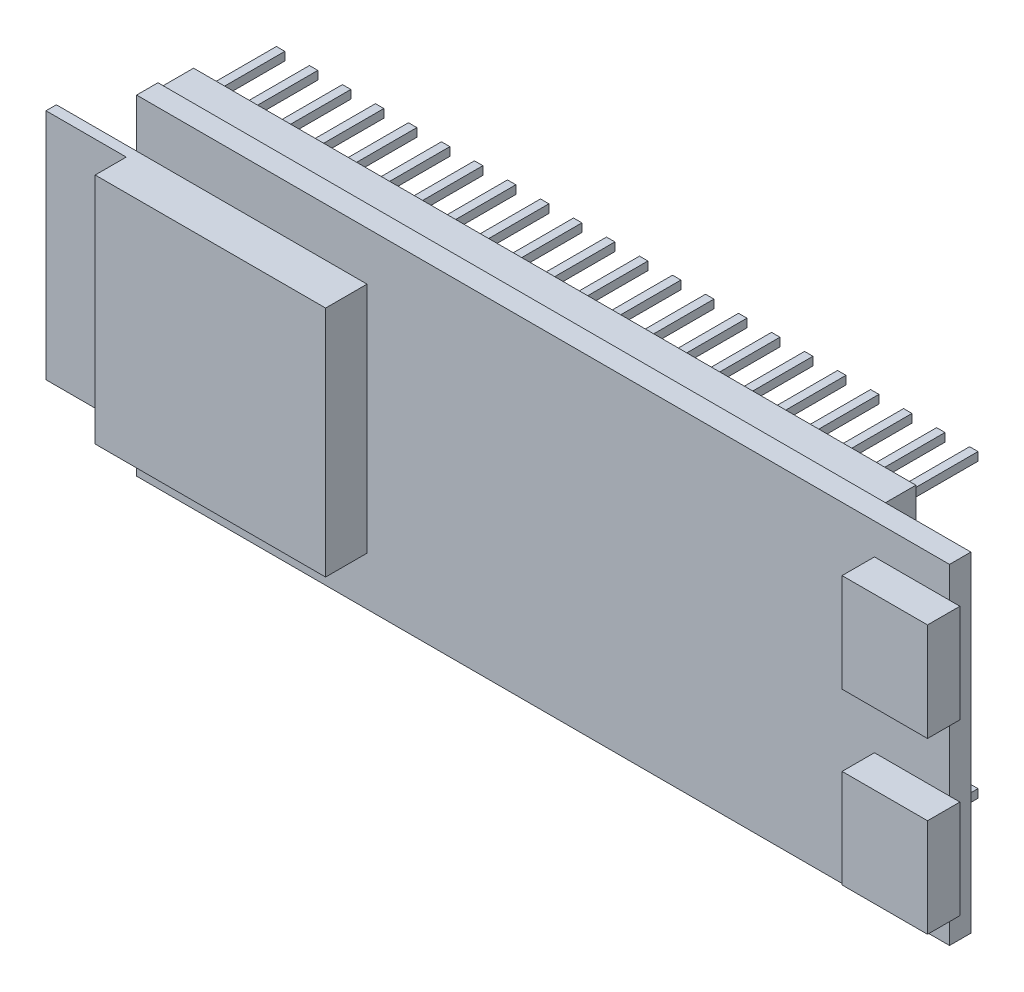
SolidWorks part; units mm, degrees
ref_plane "Front Plane" through (0, 0, 0) normal (0, 0, 1) x (1, 0, 0)
ref_plane "Top Plane" through (0, 0, 0) normal (0, 1, 0) x (1, 0, 0)
ref_plane "Right Plane" through (0, 0, 0) normal (1, 0, 0) x (0, 0, -1)
sketch "Sketch1" plane through (0, 0, 0) normal (0, 0, 1) x (1, 0, 0)
  line L1 (-31.4, 12.75) -> (31.4, 12.75)
  line L2 (-31.4, 12.75) -> (-31.4, -12.75)
  line L3 (-31.4, -12.75) -> (31.4, -12.75)
  line L4 (31.4, 12.75) -> (31.4, -12.75)
  line L5 (-31.4, 12.75) -> (31.4, -12.75) construction
  line L6 (-31.4, -12.75) -> (31.4, 12.75) construction
  point P0 (0, 0)
  dimension "D1" = 62.8
  dimension "D2" = 25.5
extrude "Boss-Extrude1" add sketch "Sketch1" along normal mid plane 1.65
sketch "Sketch2" plane through (0, 0, 0.825) normal (0, 0, 1) x (1, 0, 0)
  line L0 (0, 0) -> (-31.4, 0) construction
  line L2 (-37.6, 9) -> (-25.2, 9)
  line L3 (-37.6, 9) -> (-37.6, -9)
  line L4 (31.4, -12.75) -> (31.4, 12.75)
  line L5 (31.4, 12.75) -> (-31.4, 12.75)
  line L6 (-31.4, 12.75) -> (-31.4, -12.75)
  line L7 (-31.4, -12.75) -> (31.4, -12.75)
  line L8 (31.4, -12.75) -> (31.4, 12.75)
  line L9 (31.4, 12.75) -> (-31.4, 12.75)
  line L10 (-31.4, 12.75) -> (-31.4, -12.75)
  line L11 (-31.4, -12.75) -> (31.4, -12.75)
  line L12 (-37.6, -9) -> (-25.2, -9)
  line L13 (-25.2, 9) -> (-25.2, -9)
  line L14 (-37.6, 9) -> (-25.2, -9) construction
  line L15 (-37.6, -9) -> (-25.2, 9) construction
  line L16 (-31.4, 9) -> (-13.6, 9)
  line L17 (-31.4, 9) -> (-31.4, -9)
  line L18 (-31.4, -9) -> (-13.6, -9)
  line L19 (-13.6, 9) -> (-13.6, -9)
  line L20 (-31.4, 9) -> (-13.6, -9) construction
  line L21 (-31.4, -9) -> (-13.6, 9) construction
  point P11 (-22.5, 0)
  line M15 (-31.4, 12.75) -> (-31.4, -12.75)
  dimension "D2" = 6.2
  dimension "D3" = 18
  dimension "D4" = 17.8
  dimension "D5" = 18
  dimension "D1" = 0
extrude "Boss-Extrude2" add sketch "Sketch2" along normal blind 0.8 contours L3 L12 L2 M15 | L13 L2 L12 M15 | L19 L16 L13 L18
sketch "Sketch3" plane through (0, 0, 1.625) normal (0, 0, 1) x (1, 0, 0)
  line L4 (-13.6, 9) -> (-31.4, 9)
  line L5 (-13.6, -9) -> (-13.6, 9)
  line L6 (-31.4, -9) -> (-13.6, -9)
  line L7 (-31.4, 9) -> (-31.4, -9)
  line L8 (-13.6, 9) -> (-31.4, 9)
  line L9 (-13.6, -9) -> (-13.6, 9)
  line L10 (-31.4, -9) -> (-13.6, -9)
  line L11 (-31.4, 9) -> (-31.4, -9)
  line L12 (31.4, -12.75) -> (31.4, 12.75)
  line L13 (31.4, 12.75) -> (-31.4, 12.75)
  line L14 (-31.4, 12.75) -> (-31.4, -12.75)
  line L15 (-31.4, -12.75) -> (31.4, -12.75)
  line L16 (31.4, -12.75) -> (31.4, 12.75)
  line L17 (31.4, 12.75) -> (-31.4, 12.75)
  line L18 (-31.4, 12.75) -> (-31.4, -12.75)
  line L19 (-31.4, -12.75) -> (31.4, -12.75)
  line L20 (-25.2, 9) -> (-37.6, 9)
  line L21 (-25.2, -9) -> (-25.2, 9)
  line L22 (-37.6, -9) -> (-25.2, -9)
  line L23 (-37.6, 9) -> (-37.6, -9)
  line L24 (-25.2, 9) -> (-37.6, 9)
  line L25 (-25.2, -9) -> (-25.2, 9)
  line L26 (-37.6, -9) -> (-25.2, -9)
  line L27 (-37.6, 9) -> (-37.6, -9)
  line M14 (-37.6, -9) -> (-13.6, -9)
  line M15 (-13.6, -9) -> (-13.6, 9)
  line M16 (-13.6, 9) -> (-37.6, 9)
  dimension "D1" = 0
  dimension "D2" = 0
  dimension "D3" = 0
extrude "Boss-Extrude3" add sketch "Sketch3" along normal offset from surface (2.4 mm away) 3.2 contours L25 L8 L11 M14 | L25 L10 M15 M16 up to face at (-11.25, 0, 0.825) offset beyond the face yes
sketch "Sketch5" plane through (0, 0, 0.825) normal (0, 0, 1) x (1, 0, 0)
  line L0 (0, 0) -> (31.4, 0) construction
  line L1 (31.4, -12.75) -> (31.4, 12.75) construction
  line L2 (28.9, 12.75) -> (28.9, 0) construction
  line L3 (31.4, 12.75) -> (-31.4, 12.75) construction
  line L4 (25.6, -2.75) -> (32.2, -2.75)
  line L5 (25.6, 10.35) -> (32.2, 10.35)
  line L6 (25.6, 10.35) -> (25.6, 2.75)
  line L7 (25.6, 2.75) -> (32.2, 2.75)
  line L8 (32.2, 10.35) -> (32.2, 2.75)
  line L9 (25.6, 10.35) -> (32.2, 2.75) construction
  line L10 (25.6, 2.75) -> (32.2, 10.35) construction
  line L11 (32.2, -10.35) -> (32.2, -2.75)
  line L12 (25.6, -10.35) -> (32.2, -10.35)
  line L13 (25.6, -10.35) -> (25.6, -2.75)
  point P9 (28.9, 6.55)
  dimension "D1" = 7.6
  dimension "D2" = 6.6
  dimension "D3" = 0.8
  dimension "D4" = 2.4
extrude "Boss-Extrude4" add sketch "Sketch5" along normal blind 2.5
sketch "Sketch6" plane through (0, 0, -0.825) normal (0, 0, -1) x (-1, 0, 0)
  line L0 (-31.2, 12.55) -> (-31.2, -12.55)
  line L1 (-31.2, -12.55) -> (31.2, -12.55)
  line L2 (31.2, -12.55) -> (31.2, 12.55)
  line L3 (31.2, 12.55) -> (-31.2, 12.55)
  line L4 (-31.4, 12.75) -> (-31.4, -12.75)
  line L5 (-31.4, -12.75) -> (31.4, -12.75)
  line L6 (31.4, -12.75) -> (31.4, 12.75)
  line L7 (31.4, 12.75) -> (-31.4, 12.75)
  line L8 (-31.4, 12.75) -> (-31.4, -12.75) construction
  line L9 (-31.4, -12.75) -> (31.4, -12.75) construction
  line L10 (31.4, -12.75) -> (31.4, 12.75) construction
  line L11 (31.4, 12.75) -> (-31.4, 12.75) construction
  line L12 (-31.2, 10) -> (31.2, 10)
  line L13 (-31.2, 0) -> (31.2, 0) construction
  line L14 (-31.2, -10) -> (31.2, -10)
  dimension "D3" = 2.55
  dimension "D1" = 0
  dimension "D2" = 0.2
extrude "Boss-Extrude5" add sketch "Sketch6" along normal blind 2.55 contours L0 L12 L2 L3 | L14 L0 L1 L2
sketch "Sketch7" plane through (0, 0, -3.375) normal (0, 0, -1) x (-1, 0, 0)
  line L0 (31.2, -10) -> (-31.2, -10) construction
  line L1 (-31.2, -10) -> (-31.2, -12.55) construction
  line L2 (-31.2, -12.55) -> (31.2, -12.55) construction
  line L3 (31.2, -12.55) -> (31.2, -10) construction
  line L4 (-31.2, 12.55) -> (-31.2, 10) construction
  line L5 (-31.2, 10) -> (31.2, 10) construction
  line L6 (31.2, 10) -> (31.2, 12.55) construction
  line L7 (31.2, 12.55) -> (-31.2, 12.55) construction
  line L8 (31.2, -10) -> (-31.2, -10) construction
  line L9 (-31.2, -10) -> (-31.2, -12.55) construction
  line L10 (-31.2, -12.55) -> (31.2, -12.55) construction
  line L11 (31.2, -12.55) -> (31.2, -10) construction
  line L12 (-31.2, 12.55) -> (-31.2, 10) construction
  line L13 (-31.2, 10) -> (31.2, 10) construction
  line L14 (31.2, 10) -> (31.2, 12.55) construction
  line L15 (31.2, 12.55) -> (-31.2, 12.55) construction
  line L16 (-31.2, 11.275) -> (31.2, 11.275) construction
  line L17 (-21.25, 11.6) -> (-21.25, 10.95)
  line L18 (-23.8, 11.6) -> (-23.15, 11.6)
  line L19 (-23.8, 11.6) -> (-23.8, 10.95)
  line L20 (-23.8, 10.95) -> (-23.15, 10.95)
  line L21 (-23.15, 11.6) -> (-23.15, 10.95)
  line L22 (-23.8, 11.6) -> (-23.15, 10.95) construction
  line L23 (-23.8, 10.95) -> (-23.15, 11.6) construction
  line L24 (-21.25, 11.6) -> (-20.6, 11.6)
  line L25 (-20.6, 11.6) -> (-20.6, 10.95)
  line L26 (-21.25, 10.95) -> (-20.6, 10.95)
  line L27 (-18.7, 11.6) -> (-18.7, 10.95)
  line L28 (-18.7, 11.6) -> (-18.05, 11.6)
  line L29 (-18.05, 11.6) -> (-18.05, 10.95)
  line L30 (-18.7, 10.95) -> (-18.05, 10.95)
  line L31 (-16.15, 11.6) -> (-16.15, 10.95)
  line L32 (-16.15, 11.6) -> (-15.5, 11.6)
  line L33 (-15.5, 11.6) -> (-15.5, 10.95)
  line L34 (-16.15, 10.95) -> (-15.5, 10.95)
  line L35 (-13.6, 11.6) -> (-13.6, 10.95)
  line L36 (-13.6, 11.6) -> (-12.95, 11.6)
  line L37 (-12.95, 11.6) -> (-12.95, 10.95)
  line L38 (-13.6, 10.95) -> (-12.95, 10.95)
  line L39 (-11.05, 11.6) -> (-11.05, 10.95)
  line L40 (-11.05, 11.6) -> (-10.4, 11.6)
  line L41 (-10.4, 11.6) -> (-10.4, 10.95)
  line L42 (-11.05, 10.95) -> (-10.4, 10.95)
  line L43 (-8.5, 11.6) -> (-8.5, 10.95)
  line L44 (-8.5, 11.6) -> (-7.85, 11.6)
  line L45 (-7.85, 11.6) -> (-7.85, 10.95)
  line L46 (-8.5, 10.95) -> (-7.85, 10.95)
  line L47 (-5.95, 11.6) -> (-5.95, 10.95)
  line L48 (-5.95, 11.6) -> (-5.3, 11.6)
  line L49 (-5.3, 11.6) -> (-5.3, 10.95)
  line L50 (-5.95, 10.95) -> (-5.3, 10.95)
  line L51 (-3.4, 11.6) -> (-3.4, 10.95)
  line L52 (-3.4, 11.6) -> (-2.75, 11.6)
  line L53 (-2.75, 11.6) -> (-2.75, 10.95)
  line L54 (-3.4, 10.95) -> (-2.75, 10.95)
  line L55 (-0.85, 11.6) -> (-0.85, 10.95)
  line L56 (-0.85, 11.6) -> (-0.2, 11.6)
  line L57 (-0.2, 11.6) -> (-0.2, 10.95)
  line L58 (-0.85, 10.95) -> (-0.2, 10.95)
  line L59 (1.7, 11.6) -> (1.7, 10.95)
  line L60 (1.7, 11.6) -> (2.35, 11.6)
  line L61 (2.35, 11.6) -> (2.35, 10.95)
  line L62 (1.7, 10.95) -> (2.35, 10.95)
  line L63 (4.25, 11.6) -> (4.25, 10.95)
  line L64 (4.25, 11.6) -> (4.9, 11.6)
  line L65 (4.9, 11.6) -> (4.9, 10.95)
  line L66 (4.25, 10.95) -> (4.9, 10.95)
  line L67 (6.8, 11.6) -> (6.8, 10.95)
  line L68 (6.8, 11.6) -> (7.45, 11.6)
  line L69 (7.45, 11.6) -> (7.45, 10.95)
  line L70 (6.8, 10.95) -> (7.45, 10.95)
  line L71 (9.35, 11.6) -> (9.35, 10.95)
  line L72 (9.35, 11.6) -> (10, 11.6)
  line L73 (10, 11.6) -> (10, 10.95)
  line L74 (9.35, 10.95) -> (10, 10.95)
  line L75 (11.9, 11.6) -> (11.9, 10.95)
  line L76 (11.9, 11.6) -> (12.55, 11.6)
  line L77 (12.55, 11.6) -> (12.55, 10.95)
  line L78 (11.9, 10.95) -> (12.55, 10.95)
  line L79 (14.45, 11.6) -> (14.45, 10.95)
  line L80 (14.45, 11.6) -> (15.1, 11.6)
  line L81 (15.1, 11.6) -> (15.1, 10.95)
  line L82 (14.45, 10.95) -> (15.1, 10.95)
  line L83 (17, 11.6) -> (17, 10.95)
  line L84 (17, 11.6) -> (17.65, 11.6)
  line L85 (17.65, 11.6) -> (17.65, 10.95)
  line L86 (17, 10.95) -> (17.65, 10.95)
  line L87 (19.55, 11.6) -> (19.55, 10.95)
  line L88 (19.55, 11.6) -> (20.2, 11.6)
  line L89 (20.2, 11.6) -> (20.2, 10.95)
  line L90 (19.55, 10.95) -> (20.2, 10.95)
  line L91 (22.1, 11.6) -> (22.1, 10.95)
  line L92 (22.1, 11.6) -> (22.75, 11.6)
  line L93 (22.75, 11.6) -> (22.75, 10.95)
  line L94 (22.1, 10.95) -> (22.75, 10.95)
  line L95 (24.65, 11.6) -> (24.65, 10.95)
  line L96 (24.65, 11.6) -> (25.3, 11.6)
  line L97 (25.3, 11.6) -> (25.3, 10.95)
  line L98 (24.65, 10.95) -> (25.3, 10.95)
  line L99 (27.2, 11.6) -> (27.2, 10.95)
  line L100 (27.2, 11.6) -> (27.85, 11.6)
  line L101 (27.85, 11.6) -> (27.85, 10.95)
  line L102 (27.2, 10.95) -> (27.85, 10.95)
  line L103 (29.75, 11.6) -> (29.75, 10.95)
  line L104 (29.75, 11.6) -> (30.4, 11.6)
  line L105 (30.4, 11.6) -> (30.4, 10.95)
  line L106 (29.75, 10.95) -> (30.4, 10.95)
  line L107 (0, 0) -> (31.4, 0) construction
  line L108 (31.4, 9) -> (31.4, -9) construction
  line L109 (-23.8, -10.95) -> (-23.15, -11.6) construction
  line L110 (-23.8, -11.6) -> (-23.15, -10.95) construction
  line L111 (31.2, -10) -> (31.2, -12.55) construction
  line L112 (29.75, -10.95) -> (30.4, -10.95)
  line L113 (30.4, -11.6) -> (30.4, -10.95)
  line L114 (29.75, -11.6) -> (30.4, -11.6)
  line L115 (29.75, -11.6) -> (29.75, -10.95)
  line L116 (27.2, -10.95) -> (27.85, -10.95)
  line L117 (27.85, -11.6) -> (27.85, -10.95)
  line L118 (27.2, -11.6) -> (27.85, -11.6)
  line L119 (27.2, -11.6) -> (27.2, -10.95)
  line L120 (24.65, -10.95) -> (25.3, -10.95)
  line L121 (25.3, -11.6) -> (25.3, -10.95)
  line L122 (24.65, -11.6) -> (25.3, -11.6)
  line L123 (24.65, -11.6) -> (24.65, -10.95)
  line L124 (22.1, -10.95) -> (22.75, -10.95)
  line L125 (22.75, -11.6) -> (22.75, -10.95)
  line L126 (22.1, -11.6) -> (22.75, -11.6)
  line L127 (22.1, -11.6) -> (22.1, -10.95)
  line L128 (19.55, -10.95) -> (20.2, -10.95)
  line L129 (20.2, -11.6) -> (20.2, -10.95)
  line L130 (19.55, -11.6) -> (20.2, -11.6)
  line L131 (19.55, -11.6) -> (19.55, -10.95)
  line L132 (17, -10.95) -> (17.65, -10.95)
  line L133 (17.65, -11.6) -> (17.65, -10.95)
  line L134 (17, -11.6) -> (17.65, -11.6)
  line L135 (17, -11.6) -> (17, -10.95)
  line L136 (14.45, -10.95) -> (15.1, -10.95)
  line L137 (15.1, -11.6) -> (15.1, -10.95)
  line L138 (14.45, -11.6) -> (15.1, -11.6)
  line L139 (14.45, -11.6) -> (14.45, -10.95)
  line L140 (11.9, -10.95) -> (12.55, -10.95)
  line L141 (12.55, -11.6) -> (12.55, -10.95)
  line L142 (11.9, -11.6) -> (12.55, -11.6)
  line L143 (11.9, -11.6) -> (11.9, -10.95)
  line L144 (9.35, -10.95) -> (10, -10.95)
  line L145 (10, -11.6) -> (10, -10.95)
  line L146 (9.35, -11.6) -> (10, -11.6)
  line L147 (9.35, -11.6) -> (9.35, -10.95)
  line L148 (6.8, -10.95) -> (7.45, -10.95)
  line L149 (7.45, -11.6) -> (7.45, -10.95)
  line L150 (6.8, -11.6) -> (7.45, -11.6)
  line L151 (6.8, -11.6) -> (6.8, -10.95)
  line L152 (4.25, -10.95) -> (4.9, -10.95)
  line L153 (4.9, -11.6) -> (4.9, -10.95)
  line L154 (4.25, -11.6) -> (4.9, -11.6)
  line L155 (4.25, -11.6) -> (4.25, -10.95)
  line L156 (1.7, -10.95) -> (2.35, -10.95)
  line L157 (2.35, -11.6) -> (2.35, -10.95)
  line L158 (1.7, -11.6) -> (2.35, -11.6)
  line L159 (1.7, -11.6) -> (1.7, -10.95)
  line L160 (-0.85, -10.95) -> (-0.2, -10.95)
  line L161 (-0.2, -11.6) -> (-0.2, -10.95)
  line L162 (-0.85, -11.6) -> (-0.2, -11.6)
  line L163 (-0.85, -11.6) -> (-0.85, -10.95)
  line L164 (-3.4, -10.95) -> (-2.75, -10.95)
  line L165 (-2.75, -11.6) -> (-2.75, -10.95)
  line L166 (-3.4, -11.6) -> (-2.75, -11.6)
  line L167 (-3.4, -11.6) -> (-3.4, -10.95)
  line L168 (-5.95, -10.95) -> (-5.3, -10.95)
  line L169 (-5.3, -11.6) -> (-5.3, -10.95)
  line L170 (-5.95, -11.6) -> (-5.3, -11.6)
  line L171 (-5.95, -11.6) -> (-5.95, -10.95)
  line L172 (-8.5, -10.95) -> (-7.85, -10.95)
  line L173 (-7.85, -11.6) -> (-7.85, -10.95)
  line L174 (-8.5, -11.6) -> (-7.85, -11.6)
  line L175 (-8.5, -11.6) -> (-8.5, -10.95)
  line L176 (-11.05, -10.95) -> (-10.4, -10.95)
  line L177 (-10.4, -11.6) -> (-10.4, -10.95)
  line L178 (-11.05, -11.6) -> (-10.4, -11.6)
  line L179 (-11.05, -11.6) -> (-11.05, -10.95)
  line L180 (-13.6, -10.95) -> (-12.95, -10.95)
  line L181 (-12.95, -11.6) -> (-12.95, -10.95)
  line L182 (-13.6, -11.6) -> (-12.95, -11.6)
  line L183 (-13.6, -11.6) -> (-13.6, -10.95)
  line L184 (-16.15, -10.95) -> (-15.5, -10.95)
  line L185 (-15.5, -11.6) -> (-15.5, -10.95)
  line L186 (-16.15, -11.6) -> (-15.5, -11.6)
  line L187 (-16.15, -11.6) -> (-16.15, -10.95)
  line L188 (-18.7, -10.95) -> (-18.05, -10.95)
  line L189 (-18.05, -11.6) -> (-18.05, -10.95)
  line L190 (-18.7, -11.6) -> (-18.05, -11.6)
  line L191 (-18.7, -11.6) -> (-18.7, -10.95)
  line L192 (-21.25, -10.95) -> (-20.6, -10.95)
  line L193 (-20.6, -11.6) -> (-20.6, -10.95)
  line L194 (-21.25, -11.6) -> (-20.6, -11.6)
  line L195 (-23.15, -11.6) -> (-23.15, -10.95)
  line L196 (-23.8, -10.95) -> (-23.15, -10.95)
  line L197 (-23.8, -11.6) -> (-23.8, -10.95)
  line L198 (-23.8, -11.6) -> (-23.15, -11.6)
  line L199 (-21.25, -11.6) -> (-21.25, -10.95)
  point P6 (-23.475, 11.275)
  point P194 (-23.475, -11.275)
  dimension "D1" = 0.65
  dimension "D2" = 0.65
  dimension "D3" = 0.8
  dimension "D5" = 1.9
  dimension "D4" = 22
extrude "Boss-Extrude6" add sketch "Sketch7" along normal blind 5.6
sketch "Sketch8" plane through (0, 0, -0.825) normal (0, 0, -1) x (-1, 0, 0)
  line L0 (31.2, -10) -> (-31.2, -10) construction
  line L1 (-31.2, -10) -> (-31.2, -12.55) construction
  line L2 (-31.2, -12.55) -> (31.2, -12.55) construction
  line L3 (31.2, -12.55) -> (31.2, -10) construction
  line L4 (-31.2, 12.55) -> (-31.2, 10) construction
  line L5 (-31.2, 10) -> (31.2, 10) construction
  line L6 (31.2, 10) -> (31.2, 12.55) construction
  line L7 (31.2, 12.55) -> (-31.2, 12.55) construction
  line L8 (31.2, -10) -> (-31.2, -10)
  line L9 (-31.2, -10) -> (-31.2, -12.55)
  line L10 (-31.2, -12.55) -> (31.2, -12.55)
  line L11 (31.2, -12.55) -> (31.2, -10)
  line L12 (-31.2, 12.55) -> (-31.2, 10)
  line L13 (-31.2, 10) -> (31.2, 10)
  line L14 (31.2, 10) -> (31.2, 12.55)
  line L15 (31.2, 12.55) -> (-31.2, 12.55)
  line L16 (-24.6, 12.55) -> (-24.6, -12.55)
  line L17 (-23.8, 11.6) -> (-23.8, 10.95) construction
  line M6 (-31.2, -12.55) -> (-31.2, -10)
  line M7 (-31.2, -10) -> (31.2, -10)
  line M14 (-31.2, 10) -> (-31.2, 12.55)
  line M15 (-31.2, 12.55) -> (31.2, 12.55)
  dimension "D1" = 0.8
extrude "Cut-Extrude1" cut sketch "Sketch8" along normal through all contours L16 L13 M15 M14 | L16 L10 M7 M6
sketch "Sketch9" plane through (0, 0, 0) normal (0, 0, 1) x (1, 0, 0)
  line L0 (32.2, 2.75) -> (32.2, 10.35) construction
  line L1 (32.2, 10.35) -> (25.6, 10.35) construction
  line L2 (25.6, 10.35) -> (25.6, 2.75) construction
  line L3 (25.6, 2.75) -> (32.2, 2.75) construction
  line L4 (25.6, -2.75) -> (25.6, -10.35) construction
  line L5 (25.6, -10.35) -> (32.2, -10.35) construction
  line L6 (32.2, -10.35) -> (32.2, -2.75) construction
  line L7 (32.2, -2.75) -> (25.6, -2.75) construction
  line L8 (-31.4, -9) -> (-31.4, 9) construction
  line L9 (-31.4, 9) -> (-37.6, 9) construction
  line L10 (-37.6, 9) -> (-37.6, -9) construction
  line L11 (-37.6, -9) -> (-31.4, -9) construction
  line L12 (31.4, -12.75) -> (31.4, -10.35) construction
  line L13 (31.4, -10.35) -> (25.6, -10.35) construction
  line L14 (25.6, -10.35) -> (25.6, -2.75) construction
  line L15 (25.6, -2.75) -> (31.4, -2.75) construction
  line L16 (31.4, -2.75) -> (31.4, 2.75) construction
  line L17 (31.4, 2.75) -> (25.6, 2.75) construction
  line L18 (25.6, 2.75) -> (25.6, 10.35) construction
  line L19 (25.6, 10.35) -> (31.4, 10.35) construction
  line L20 (31.4, 10.35) -> (31.4, 12.75) construction
  line L21 (31.4, 12.75) -> (-31.4, 12.75) construction
  line L22 (-31.4, 12.75) -> (-31.4, 9) construction
  line L23 (-31.4, 9) -> (-13.6, 9) construction
  line L24 (-13.6, 9) -> (-13.6, -9) construction
  line L25 (-13.6, -9) -> (-31.4, -9) construction
  line L26 (-31.4, -9) -> (-31.4, -12.75) construction
  line L27 (-31.4, -12.75) -> (31.4, -12.75) construction
  line L28 (32.2, 2.75) -> (32.2, 10.35) construction
  line L29 (32.2, 10.35) -> (25.6, 10.35) construction
  line L30 (25.6, 10.35) -> (25.6, 2.75) construction
  line L31 (25.6, 2.75) -> (32.2, 2.75) construction
  line L32 (25.6, -2.75) -> (25.6, -10.35) construction
  line L33 (25.6, -10.35) -> (32.2, -10.35) construction
  line L34 (32.2, -10.35) -> (32.2, -2.75) construction
  line L35 (32.2, -2.75) -> (25.6, -2.75) construction
  line L36 (-31.4, -9) -> (-31.4, 9) construction
  line L37 (-31.4, 9) -> (-37.6, 9) construction
  line L38 (-37.6, 9) -> (-37.6, -9) construction
  line L39 (-37.6, -9) -> (-31.4, -9) construction
  line L40 (31.4, -12.75) -> (31.4, -10.35) construction
  line L41 (31.4, -10.35) -> (25.6, -10.35) construction
  line L42 (25.6, -10.35) -> (25.6, -2.75) construction
  line L43 (25.6, -2.75) -> (31.4, -2.75) construction
  line L44 (31.4, -2.75) -> (31.4, 2.75) construction
  line L45 (31.4, 2.75) -> (25.6, 2.75) construction
  line L46 (25.6, 2.75) -> (25.6, 10.35) construction
  line L47 (25.6, 10.35) -> (31.4, 10.35) construction
  line L48 (31.4, 10.35) -> (31.4, 12.75) construction
  line L49 (31.4, 12.75) -> (-31.4, 12.75) construction
  line L50 (-31.4, 12.75) -> (-31.4, 9) construction
  line L51 (-31.4, 9) -> (-13.6, 9) construction
  line L52 (-13.6, 9) -> (-13.6, -9) construction
  line L53 (-13.6, -9) -> (-31.4, -9) construction
  line L54 (-31.4, -9) -> (-31.4, -12.75) construction
  line L55 (-31.4, -12.75) -> (31.4, -12.75) construction
  line L56 (32.2, -2.75) -> (32.2, 2.75) construction
  line L57 (-37.6, 0) -> (32.2, 0) construction
  point P6 (-2.7, 0)
